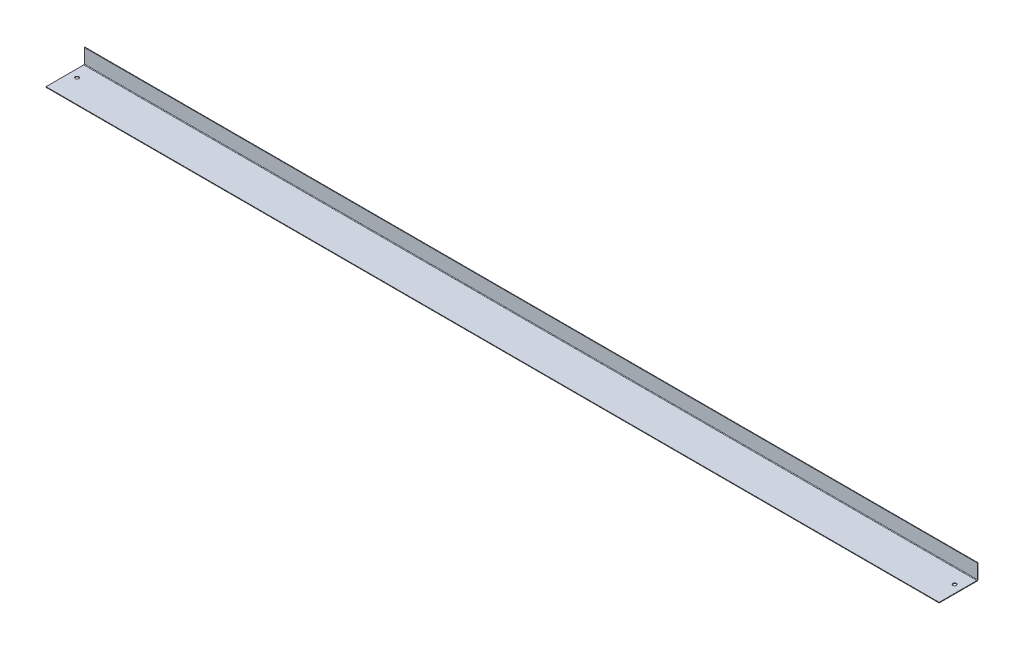
SolidWorks part; units mm, degrees
material "AISI 304"
ref_plane "Front Plane" through (0, 0, 0) normal (0, 0, 1) x (1, 0, 0)
ref_plane "Top Plane" through (0, 0, 0) normal (0, 1, 0) x (1, 0, 0)
ref_plane "Right Plane" through (0, 0, 0) normal (1, 0, 0) x (0, 0, -1)
sketch "Sketch1" plane through (0, 0, 0) normal (1, 0, 0) x (0, 0, -1)
  line L0 (63.8095, 24.2857) -> (63.8095, -15.7143)
  line L1 (63.8095, -15.7143) -> (-36.1905, -15.7143)
  dimension "D1" = 40
  dimension "D2" = 100
extrude "Extrude-Thin1" add sketch "Sketch1" along normal mid plane 2300 thin
fillet "Fillet1" radius 1.5 1 edges at (0, -14.2143, -62.3095)
fillet "Fillet2" radius 3 1 edges at (0, -15.7143, -63.8095)
sketch "Sketch2" plane through (0, -14.2143, 0) normal (0, 1, 0) x (1, 0, 0)
  line L0 (-1150, 60.8095) -> (-1150, -36.1905) construction
  line L1 (1150, 63.8095) -> (-1150, 63.8095) construction
  circle A0 centre (-1130, 23.8095) radius 4.5
  dimension "D1" = 9
  dimension "D3" = 40
  dimension "D2" = 20
extrude "Cut-Extrude1" cut sketch "Sketch2" against normal blind 10
mirror "Mirror1" about plane through (0, 0, 0) normal (1, 0, 0) of "Cut-Extrude1"
